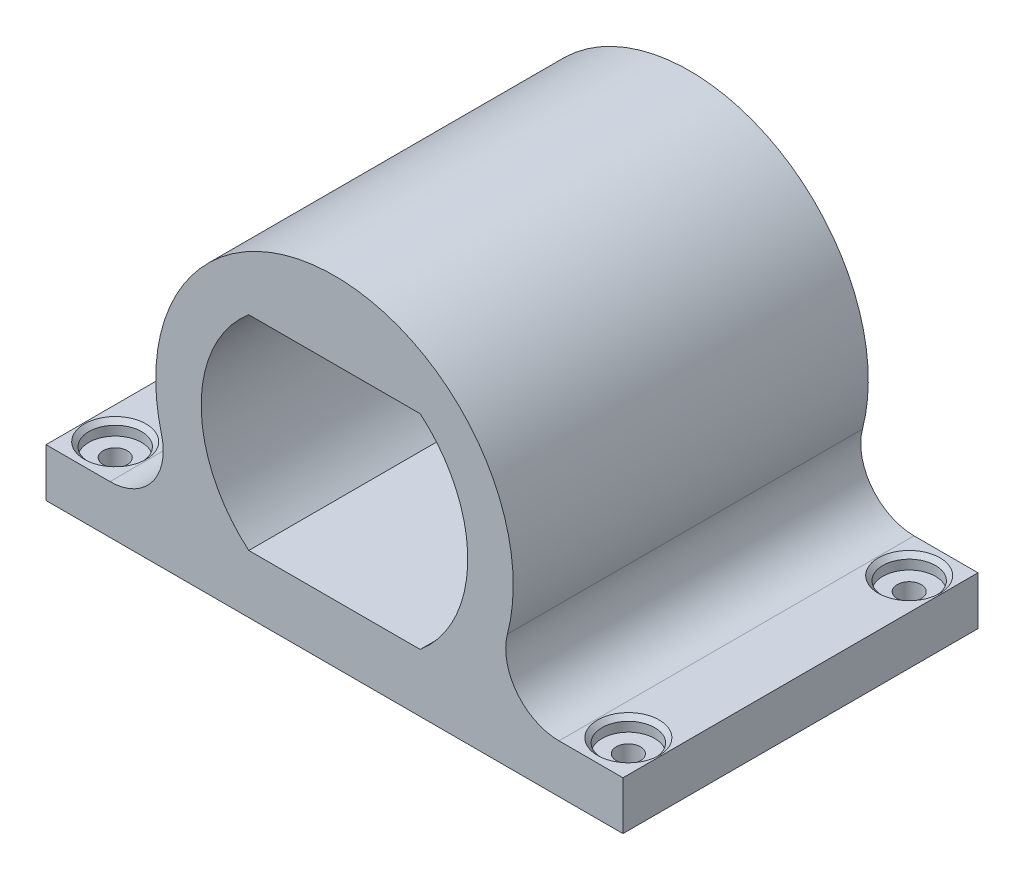
SolidWorks part; units mm, degrees
ref_plane "Front Plane" through (0, 0, 0) normal (0, 0, 1) x (1, 0, 0)
ref_plane "Top Plane" through (0, 0, 0) normal (0, 1, 0) x (1, 0, 0)
ref_plane "Right Plane" through (0, 0, 0) normal (1, 0, 0) x (0, 0, -1)
sketch "Sketch1" plane through (0, 0, 0) normal (0, 0, 1) x (1, 0, 0)
  line L0 (0, 0) -> (0, 45.304) construction
  line L1 (0, 0) -> (0, -46.0833) construction
  line L2 (0, 0) -> (50.8021, 0) construction
  line L3 (0, 0) -> (-45.2366, 0) construction
  line L4 (41.275, -15.9999) -> (41.275, -22.9235)
  line L5 (0, 14.605) -> (12.2622, 14.605)
  line L6 (41.275, -22.9235) -> (-41.275, -22.9235)
  line L7 (-41.275, -22.9235) -> (-41.275, -16.0002)
  line L8 (-41.275, -16.0002) -> (-32.1204, -16.0002)
  line L9 (41.275, -15.9999) -> (32.1207, -16.0002)
  line L11 (0, 14.605) -> (-12.2622, 14.605)
  line L13 (0, -14.605) -> (12.2622, -14.605)
  line L14 (0, -14.605) -> (-12.2622, -14.605)
  arc A0 (32.1207, -16.0002) -> (24.7473, -6.4565) centre (32.1204, -8.3802) cw
  arc A1 (12.2622, 14.605) -> (12.2622, -14.605) centre (0, 0) cw
  arc A2 (-24.7473, -6.4565) -> (24.7473, -6.4565) centre (0, 0) cw
  arc A3 (-32.1204, -16.0002) -> (-24.7473, -6.4565) centre (-32.1204, -8.3802) ccw
  arc A4 (-12.2622, 14.605) -> (-12.2622, -14.605) centre (0, 0) ccw
  point P42 (0, -22.9235)
  dimension "D1" = 7.62
  dimension "D2" = 7.62
  dimension "D6" = 82.55
extrude "Boss-Extrude1" add sketch "Sketch1" along normal blind 50.8
sketch "Sketch5" plane through (0, -16.0002, 0) normal (0, 1, 0) x (1, 0, 0)
  line L0 (-36.6977, 0) -> (-36.6977, -5.2858)
  line L1 (-32.1204, 0) -> (-41.275, 0) construction
  line L2 (-36.6977, -5.2858) -> (-41.275, -5.2858)
  line L3 (-41.275, -50.8) -> (-41.275, 0) construction
  line L4 (-32.1204, -50.8) -> (-41.275, -50.8) construction
  line L5 (-36.6977, -50.8) -> (-36.6977, -45.4757)
  line L6 (-36.6977, -45.4757) -> (-41.275, -45.4757)
hole_wizard "CBORE for #5 Binding Head Machine Screw1" positions "3DSketch1" profile "Sketch6" counterbore size "#5" standard "ANSI Inch" end condition through all
sketch3d "3DSketch1"
  point P0 (-36.6977, -16.0002, 5.2858)
  point P3 (-36.6977, -16.0002, 45.4757)
sketch "Sketch6" plane through (-36.6977, -16.0002, 5.2858) normal (1, 0, 0) x (0, 0, 1)
  line L0 (0, 0) -> (0, 6.9233)
  line L1 (0, 6.9233) -> (1.7272, 6.9233)
  line L3 (1.7272, 6.9233) -> (1.7272, 1.9812)
  line L4 (3.7706, 1.9812) -> (1.7272, 1.9812)
  line L5 (3.7706, 1.9812) -> (3.7706, 0.635)
  line L6 (3.7706, 0.635) -> (4.4056, 0)
  line L7 (4.4056, 0) -> (0, 0)
  line L8 (-3.7706, 0.635) -> (-4.4056, 0) construction
  line L11 (0, -6.35) -> (0, 107.95) construction
  dimension "Thru Hole Dia." = 3.4544
  dimension "Thru Hole Depth" = 6.9233
  dimension "C'Bore Dia." = 7.5413
  dimension "C'Bore Depth" = 1.9812
  dimension "Near C'Sink Dia." = 8.8113
  dimension "Near C'Sink Angle" = 90
sketch "Sketch7" plane through (0.0005, -16.0012, 0) normal (0, 1, 0) x (1, 0, 0)
  line L0 (36.6973, -50.8) -> (36.6973, -45.4495)
  line L1 (41.2745, -50.8) -> (32.1202, -50.8) construction
  line L2 (36.6973, -45.4495) -> (41.2745, -45.4495)
  line L3 (41.2745, -50.8) -> (41.2745, 0) construction
  line L4 (41.2745, 0) -> (32.1202, 0) construction
  line L5 (36.6973, 0) -> (36.6973, -5.268)
  line L6 (36.6973, -5.268) -> (41.2745, -5.268)
hole_wizard "CBORE for #5 Binding Head Machine Screw2" positions "3DSketch2" profile "Sketch8" counterbore size "#5" standard "ANSI Inch" end condition through all
sketch3d "3DSketch2"
  point P0 (36.6978, -16.0001, 5.268)
  point P3 (36.6978, -16.0001, 45.4495)
sketch "Sketch8" plane through (36.6978, -16.0001, 5.268) normal (0, 0, 1) x (-1, 0, 0)
  line L0 (0, 0) -> (0, 6.9236)
  line L1 (0, 6.9236) -> (1.7272, 6.9236)
  line L3 (1.7272, 6.9236) -> (1.7272, 1.9812)
  line L4 (3.7706, 1.9812) -> (1.7272, 1.9812)
  line L5 (3.7706, 1.9812) -> (3.7706, 0.635)
  line L6 (3.7706, 0.635) -> (4.4056, 0)
  line L7 (4.4056, 0) -> (0, 0)
  line L8 (-3.7706, 0.635) -> (-4.4056, 0) construction
  line L11 (0, -6.35) -> (0, 107.95) construction
  dimension "Thru Hole Dia." = 3.4544
  dimension "Thru Hole Depth" = 6.9236
  dimension "C'Bore Dia." = 7.5413
  dimension "C'Bore Depth" = 1.9812
  dimension "Near C'Sink Dia." = 8.8113
  dimension "Near C'Sink Angle" = 90
hole_wizard "CSK for #8 Flat Head Machine Screw (100)1" positions "Sketch3" profile "Sketch2" countersink size "#8" standard "ANSI Inch"
sketch "Sketch3" plane through (0, -16.0002, 0) normal (0, 1, 0) x (1, 0, 0)
  line L0 (-30.1625, -9.525) -> (30.1625, -9.525) construction
  line L1 (30.1625, -9.525) -> (30.1625, -41.275) construction
  line L2 (30.1625, -41.275) -> (-30.1625, -41.275) construction
  line L3 (-30.1625, -41.275) -> (-30.1625, -9.525) construction
  line L4 (-30.1625, -9.525) -> (30.1625, -41.275) construction
  line L6 (0, -25.4) -> (0, 0) construction
  line L8 (34.925, -50.8) -> (34.925, 0) construction
  line L9 (34.925, -50.8) -> (25.4, -50.8) construction
  line L10 (34.925, 0) -> (25.4, 0) construction
  point P4 (-30.1625, -9.525)
  point P6 (-30.1625, -41.275)
  point P8 (30.1625, -41.275)
  point P10 (30.1625, -9.525)
  dimension "D1" = 4.7625
  dimension "D2" = 9.525
  dimension "D3" = 9.525
sketch "Sketch2" plane through (-30.1625, -16.0002, 9.525) normal (1, 0, 0) x (0, 0, 1)
  line L0 (0, 0) -> (0, 6.9233)
  line L1 (0, 6.9233) -> (2.2479, 6.9233)
  line L2 (2.2479, 6.9233) -> (2.2479, 1.6518)
  line L3 (2.2479, 1.6518) -> (4.2164, 0)
  line L5 (4.2164, 0) -> (0, 0)
  line L6 (-2.2479, 1.6518) -> (-4.2164, 0) construction
  line L11 (0, -6.35) -> (0, 107.95) construction
  dimension "Thru Hole Dia." = 4.4958
  dimension "Thru Hole Depth" = 6.9233
  dimension "Near C'Sink Dia." = 8.4328
  dimension "Near C'Sink Angle" = 100
